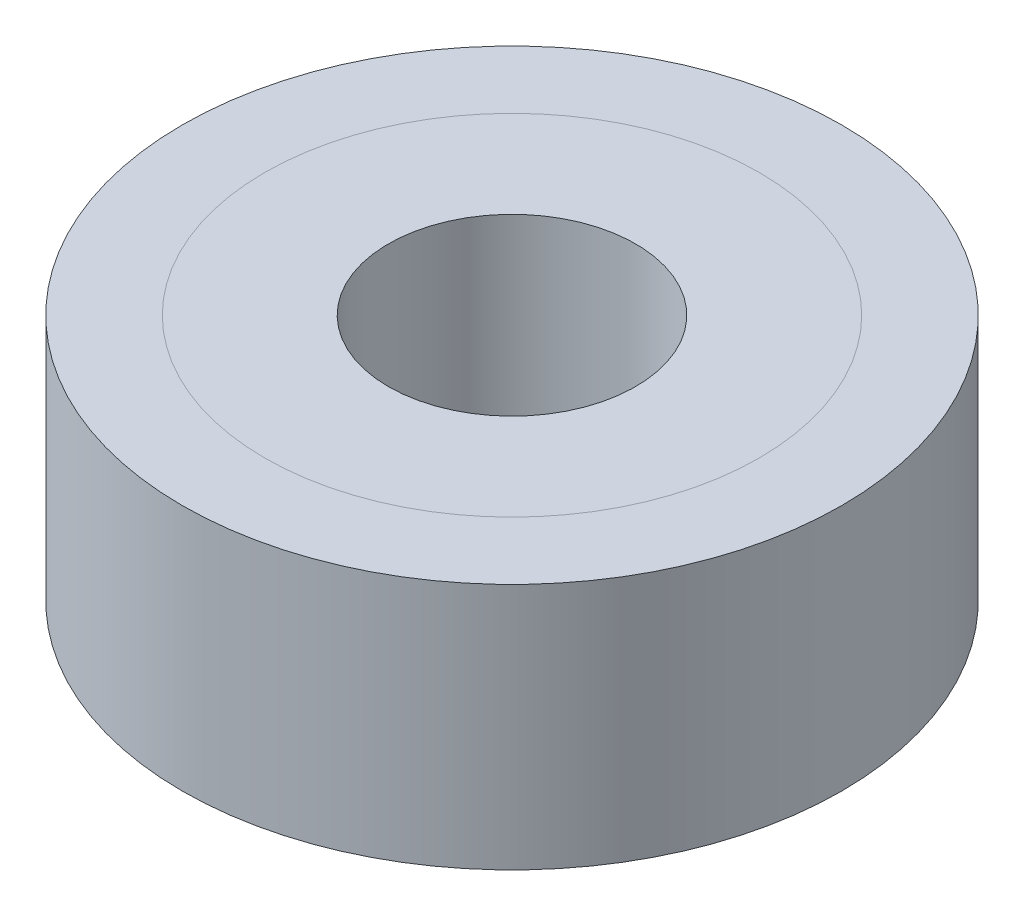
SolidWorks part; units mm, degrees
ref_plane "前视基准面" through (0, 0, 0) normal (0, 0, 1) x (1, 0, 0)
ref_plane "上视基准面" through (0, 0, 0) normal (0, 1, 0) x (1, 0, 0)
ref_plane "右视基准面" through (0, 0, 0) normal (1, 0, 0) x (0, 0, -1)
sketch "草图1" plane through (0, 0, 0) normal (0, 1, 0) x (1, 0, 0)
  circle A0 centre (0, 0) radius 4
  circle A1 centre (0, 0) radius 1.5
  dimension "D1" = 3
  dimension "D2" = 8
extrude "凸台-拉伸1" add sketch "草图1" along normal blind 3
sketch "草图2" plane through (0, 3, 0) normal (0, 1, 0) x (1, 0, 0)
  circle A0 centre (0, 0) radius 3
  dimension "D1" = 6
split "分割1" trim tools "草图2" bodies to split 106 resulting bodies 107 108
